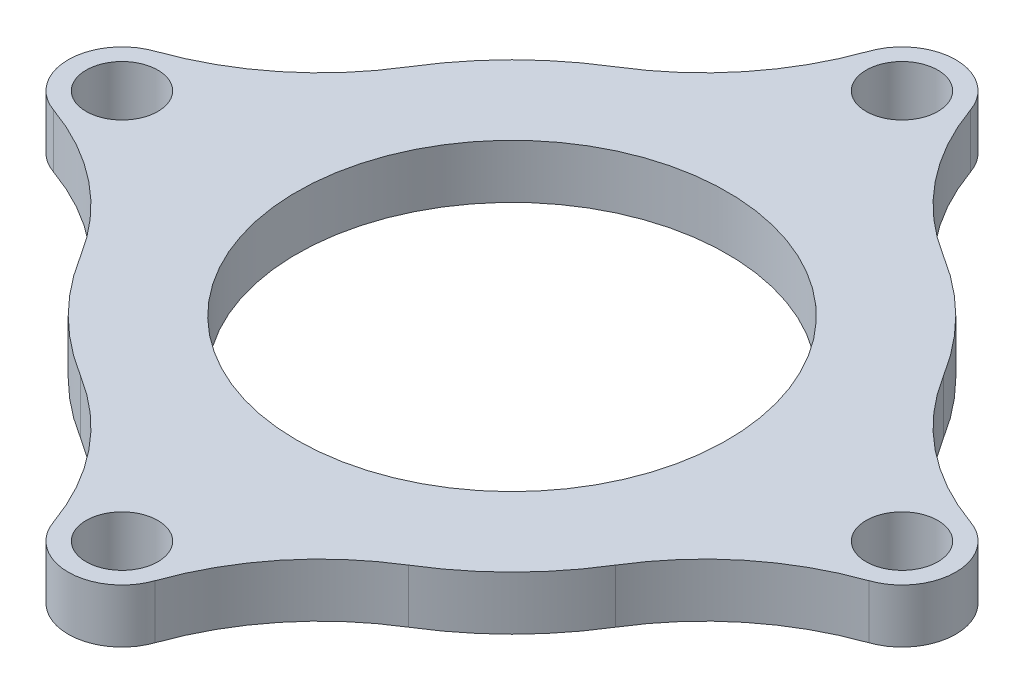
SolidWorks part; units mm, degrees
material "5052-H34"
ref_plane "正面" through (0, 0, 0) normal (0, 0, 1) x (1, 0, 0)
ref_plane "平面" through (0, 0, 0) normal (0, 1, 0) x (1, 0, 0)
ref_plane "右側面" through (0, 0, 0) normal (1, 0, 0) x (0, 0, -1)
sketch "ｽｹｯﾁ1" plane through (0, 0, 0) normal (0, 1, 0) x (1, 0, 0)
  line L0 (0, 0) -> (12.3744, 12.3744) construction
  line L1 (0, 0) -> (12, 0) construction
  arc A0 (-9.1459, 14.9199) -> (-14.9199, 9.1459) centre (0, 0) ccw
  circle A1 centre (0, 0) radius 12
  arc A2 (2.8309, 22.7431) -> (-2.8309, 22.7431) centre (0, 21.75) ccw
  circle A3 centre (0, 21.75) radius 2
  arc A4 (22.7431, -2.8309) -> (22.7431, 2.8309) centre (21.75, 0) ccw
  circle A5 centre (21.75, 0) radius 2
  arc A6 (-2.8309, -22.7431) -> (2.8309, -22.7431) centre (0, -21.75) ccw
  circle A7 centre (0, -21.75) radius 2
  arc A8 (-22.7431, 2.8309) -> (-22.7431, -2.8309) centre (-21.75, 0) ccw
  circle A9 centre (-21.75, 0) radius 2
  arc A10 (2.8309, 22.7431) -> (9.1459, 14.9199) centre (16.9852, 27.7083) ccw
  arc A11 (22.7431, 2.8309) -> (14.9199, 9.1459) centre (27.7083, 16.9852) cw
  arc A12 (2.8309, -22.7431) -> (9.1459, -14.9199) centre (16.9852, -27.7083) cw
  arc A13 (22.7431, -2.8309) -> (14.9199, -9.1459) centre (27.7083, -16.9852) ccw
  arc A14 (-22.7431, -2.8309) -> (-14.9199, -9.1459) centre (-27.7083, -16.9852) cw
  arc A15 (-2.8309, -22.7431) -> (-9.1459, -14.9199) centre (-16.9852, -27.7083) ccw
  arc A16 (-2.8309, 22.7431) -> (-9.1459, 14.9199) centre (-16.9852, 27.7083) cw
  arc A17 (-22.7431, 2.8309) -> (-14.9199, 9.1459) centre (-27.7083, 16.9852) ccw
  arc A18 (14.9199, 9.1459) -> (9.1459, 14.9199) centre (0, 0) ccw
  arc A19 (-14.9199, -9.1459) -> (-9.1459, -14.9199) centre (0, 0) ccw
  arc A20 (9.1459, -14.9199) -> (14.9199, -9.1459) centre (0, 0) ccw
  point P18 (0, 0)
  point P25 (0, 0)
  point P26 (12, 0)
  dimension "D1" = 24
  dimension "D2" = 35
  dimension "D3" = 6
  dimension "D4" = 4
  dimension "D6" = 43.5
  dimension "D7" = 15
  dimension "D5" = 4
extrude "ﾎﾞｽ - 押し出し1" add sketch "ｽｹｯﾁ1" along normal blind 3
